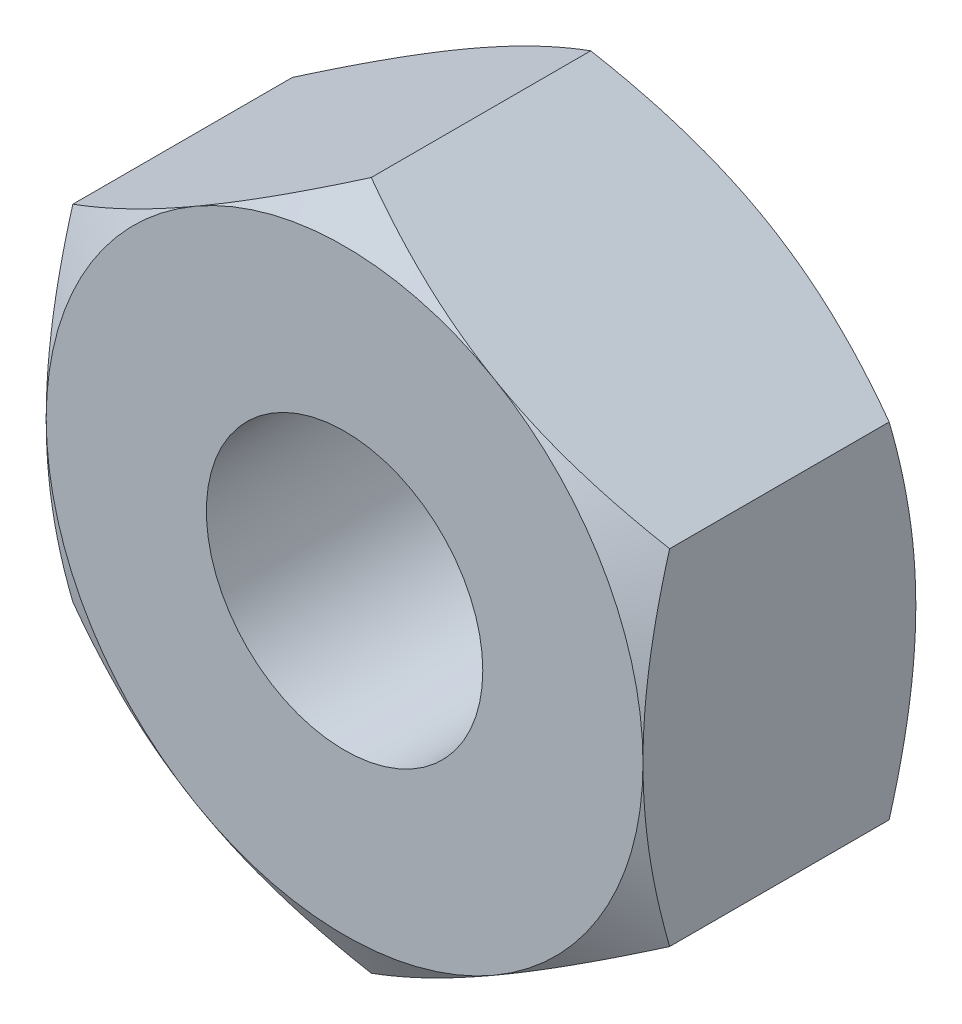
SolidWorks part; units mm, degrees
ref_plane "基准面1" through (0, 0, 0) normal (0, 0, 1) x (1, 0, 0)
ref_plane "基准面2" through (0, 0, 0) normal (0, 1, 0) x (1, 0, 0)
ref_plane "基准面3" through (0, 0, 0) normal (1, 0, 0) x (0, 0, -1)
sketch "尺寸草图" plane through (0, 0, 0) normal (0, 0, 1) x (1, 0, 0)
  line L0 (0, 0) -> (7.7, 0) construction
  line L1 (0, 0) -> (15.4, 0) construction
  line L2 (7.7, 0) -> (13.6, 0) construction
  line L3 (-3.8095, 0) -> (0, 0) construction
  point P3 (4, 0)
  point P4 (0.7, 0)
  point P5 (7.7, 0)
  point P6 (3.2, 0)
  point P8 (7, 0)
  dimension "D1" = 3.8095
  dimension "D" = 4
  dimension "P" = 0.7
  dimension "e(最小)" = 7.7
  dimension "m(最大)" = 3.2
  dimension "s(公称)" = 7
  dimension "dw(最小)" = 5.9
sketch "草图1" plane through (0, 0, 0) normal (0, 0, 1) x (1, 0, 0)
  line L0 (-3.5, 0) -> (3.5, 0) construction
  line L1 (0, 4.0415) -> (0, -4.0415) construction
  line L3 (0, 4.0415) -> (-3.5, 2.0207)
  line L4 (-3.5, 2.0207) -> (-3.5, -2.0207)
  line L5 (-3.5, -2.0207) -> (0, -4.0415)
  line L6 (0, -4.0415) -> (3.5, -2.0207)
  line L7 (3.5, -2.0207) -> (3.5, 2.0207)
  line L8 (3.5, 2.0207) -> (0, 4.0415)
  circle A0 centre (0, 0) radius 3.5 construction
  circle A1 centre (0, 0) radius 1.6211
  point P2 (0, 3.6585)
  dimension "D1" = 7.7
  dimension "D" = 3.2422
  dimension "D2" = 7
extrude "基体-拉伸" add sketch "草图1" along normal blind 3.2
cosmetic thread "装饰螺纹线1" parameters "D2"=4
sketch "草图2" plane through (0, 0, 0) normal (0, 0, -1) x (-1, 0, 0)
  circle A0 centre (0, 0) radius 3.5
  circle A1 centre (0, 0) radius 1.6211 construction
  dimension "s" = 7
extrude "切除-拉伸1" cut sketch "草图2" against normal through all draft 60 flip side to cut
sketch "草图3" plane through (0, 0, 3.2) normal (0, 0, 1) x (1, 0, 0)
  circle A0 centre (0, 0) radius 3.5
  dimension "D1" = 7
extrude "切除-拉伸2" cut sketch "草图3" against normal through all draft 60 flip side to cut
